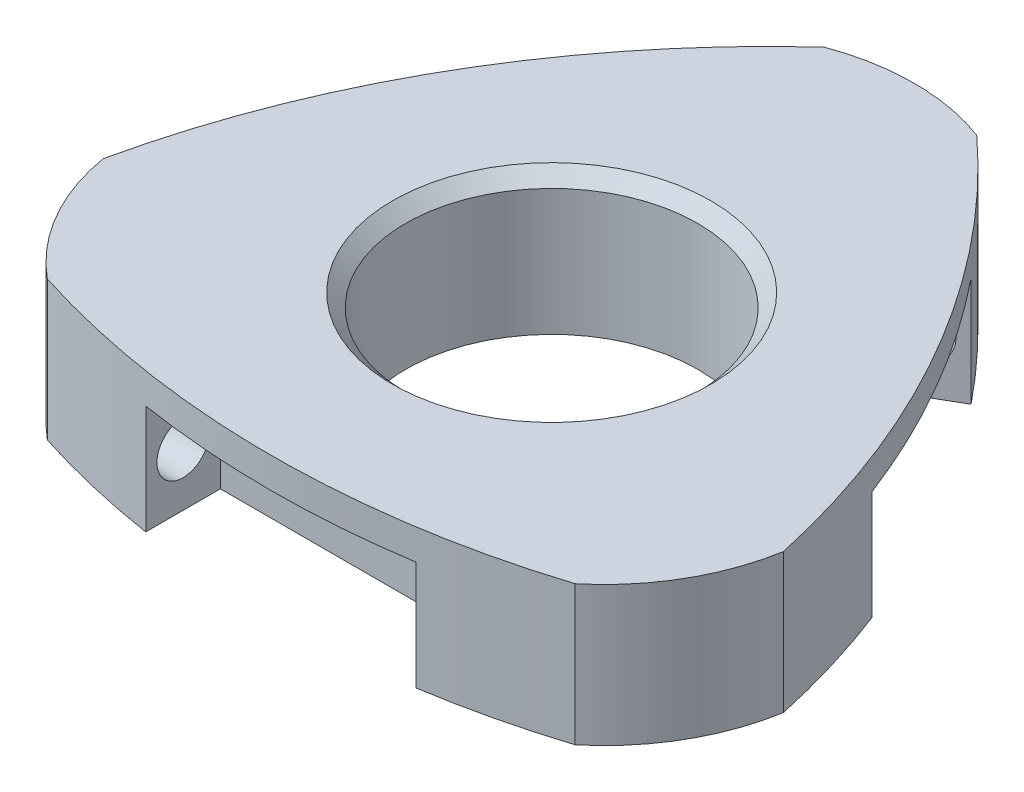
SolidWorks part; units mm, degrees
ref_plane "Front Plane" through (0, 0, 0) normal (0, 0, 1) x (1, 0, 0)
ref_plane "Top Plane" through (0, 0, 0) normal (0, 1, 0) x (1, 0, 0)
ref_plane "Right Plane" through (0, 0, 0) normal (1, 0, 0) x (0, 0, -1)
sketch "Sketch1" plane through (0, 0, 0) normal (0, 1, 0) x (1, 0, 0)
  line L0 (0, 0) -> (0, 80) construction
  line L1 (0, 0) -> (69.282, -40) construction
  line L2 (0, 0) -> (-69.282, -40) construction
  line L3 (-17.5, 80) -> (17.5, 80) construction
  line L4 (60.532, -55.1554) -> (78.032, -24.8446) construction
  line L5 (-78.032, -24.8446) -> (-60.532, -55.1554) construction
  circle A0 centre (0, 0) radius 33.5
  arc A1 (17.5, 80) -> (78.032, -24.8446) centre (-117.3155, -67.7321) cw
  arc A2 (60.532, -55.1554) -> (-60.532, -55.1554) centre (0, 135.4643) cw
  arc A3 (-78.032, -24.8446) -> (-17.5, 80) centre (117.3155, -67.7321) cw
  arc A4 (-17.5, 80) -> (17.5, 80) centre (0, 33.1625) cw
  arc A5 (78.032, -24.8446) -> (60.532, -55.1554) centre (28.7196, -16.5813) cw
  arc A6 (-60.532, -55.1554) -> (-78.032, -24.8446) centre (-28.7196, -16.5813) cw
  point P9 (0, 80)
  point P12 (69.282, -40)
  point P15 (-69.282, -40)
  dimension "D1" = 67
  dimension "D6" = 200
  dimension "D7" = 50
  dimension "D2" = 120
  dimension "D3" = 120
  dimension "D4" = 35
  dimension "D5" = 80
extrude "Boss-Extrude1" add sketch "Sketch1" along normal blind 32
chamfer "Chamfer1" distance 3 angle 45 1 edges at (0, 32, 33.5)
sketch "Sketch2" plane through (0, 0, 0) normal (0, -1, 0) x (1, 0, 0)
  line L0 (0, 0) -> (0, 55) construction
  line L1 (-31, 45) -> (31, 45)
  line L2 (-31, 45) -> (-31, 65)
  line L3 (-31, 65) -> (31, 65)
  line L4 (31, 45) -> (31, 65)
  line L5 (-31, 45) -> (31, 65) construction
  line L6 (-31, 65) -> (31, 45) construction
  point P0 (0, 55)
  dimension "D1" = 62
  dimension "D2" = 20
  dimension "D3" = 55
extrude "Cut-Extrude1" cut sketch "Sketch2" against normal blind 25
sketch "Sketch3" plane through (0, 0, 0) normal (1, 0, 0) x (0, 0, -1)
  line L0 (-62.1186, 25) -> (-62.1186, 0) construction
  line L1 (-45, 25) -> (-45, 0) construction
  line L2 (-62.1186, 25) -> (-62.1186, 0) construction
  line L3 (-45, 25) -> (-45, 0) construction
  line L4 (-45, 25) -> (-62.1186, 0) construction
  circle A0 centre (-53.5593, 12.5) radius 6
  dimension "D1" = 12
extrude "Cut-Extrude2" cut sketch "Sketch3" against normal blind 40 and the other way blind 40
pattern_circular "CirPattern1" count 3 over 360 about axis through (0, 0, 0) along (0, 1, 0) of "Cut-Extrude1", "Cut-Extrude2"
